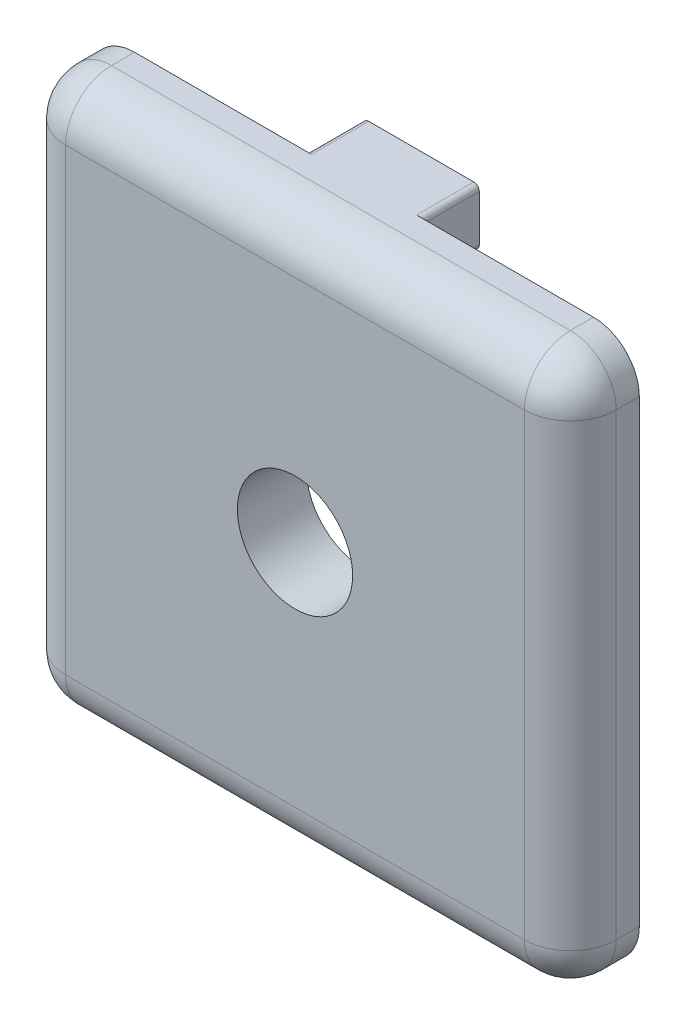
SolidWorks part; units mm, degrees
material "ABS"
ref_plane "Front Plane" through (0, 0, 0) normal (0, 0, 1) x (1, 0, 0)
ref_plane "Top Plane" through (0, 0, 0) normal (0, 1, 0) x (1, 0, 0)
ref_plane "Right Plane" through (0, 0, 0) normal (1, 0, 0) x (0, 0, -1)
sketch "Sketch1" plane through (0, 0, 0) normal (0, 0, 1) x (1, 0, 0)
  line L0 (25.1995, 20.1268) -> (26.2155, 20.1268)
  line L1 (25.7075, 19.6188) -> (25.7075, 20.6348)
  line L2 (25.1995, 20.1268) -> (26.2155, 20.1268)
  line L3 (25.7075, 19.6188) -> (25.7075, 20.6348)
  line L13 (9.8325, 39.1768) -> (41.5825, 39.1768)
  line L14 (44.7575, 36.0018) -> (44.7575, 4.2518)
  line L15 (6.6575, 36.0018) -> (6.6575, 4.2518)
  line L16 (9.8325, 1.0768) -> (41.5825, 1.0768)
  circle A0 centre (25.7075, 20.1268) radius 3.9878
  arc A3 (44.7575, 36.0018) -> (41.5825, 39.1768) centre (41.5825, 36.0018) ccw
  arc A4 (9.8325, 39.1768) -> (6.6575, 36.0018) centre (9.8325, 36.0018) ccw
  arc A5 (6.6575, 4.2518) -> (9.8325, 1.0768) centre (9.8325, 4.2518) ccw
  arc A6 (41.5825, 1.0768) -> (44.7575, 4.2518) centre (41.5825, 4.2518) ccw
  point P4 (27.5097, 22.2397)
  point P5 (23.9053, 18.0139)
extrude "Extrude1" add sketch "Sketch1" along normal blind 4.7752 contours L16 A6 L14 A3 L13 A4 L15 A5 A0
fillet "Fillet1" radius 3.175 8 edges at (7.5874, 38.2469, 4.7752) (6.6575, 20.1268, 4.7752) (7.5874, 2.0067, 4.7752) (25.7075, 1.0768, 4.7752) (43.8276, 2.0067, 4.7752) (44.7575, 20.1268, 4.7752) (43.8276, 38.2469, 4.7752) (25.7075, 39.1768, 4.7752)
sketch "Sketch2" plane through (0, 0, 0) normal (0, 0, -1) x (-1, 0, 0)
  line L0 (-29.3397, 35.2144) -> (-22.0753, 35.2144)
  line L1 (-21.6943, 38.7958) -> (-21.6943, 35.5954)
  line L2 (-29.7207, 38.7958) -> (-29.7207, 35.5954)
  line L3 (-22.0753, 39.1768) -> (-29.3397, 39.1768)
  arc A1 (-22.0753, 35.2144) -> (-21.6943, 35.5954) centre (-22.0753, 35.5954) ccw
  arc A2 (-21.6943, 38.7958) -> (-22.0753, 39.1768) centre (-22.0753, 38.7958) ccw
  arc A3 (-29.7207, 35.5954) -> (-29.3397, 35.2144) centre (-29.3397, 35.5954) ccw
  arc A4 (-29.3397, 39.1768) -> (-29.7207, 38.7958) centre (-29.3397, 38.7958) ccw
extrude "Extrude2" add sketch "Sketch2" along normal blind 3.9624
